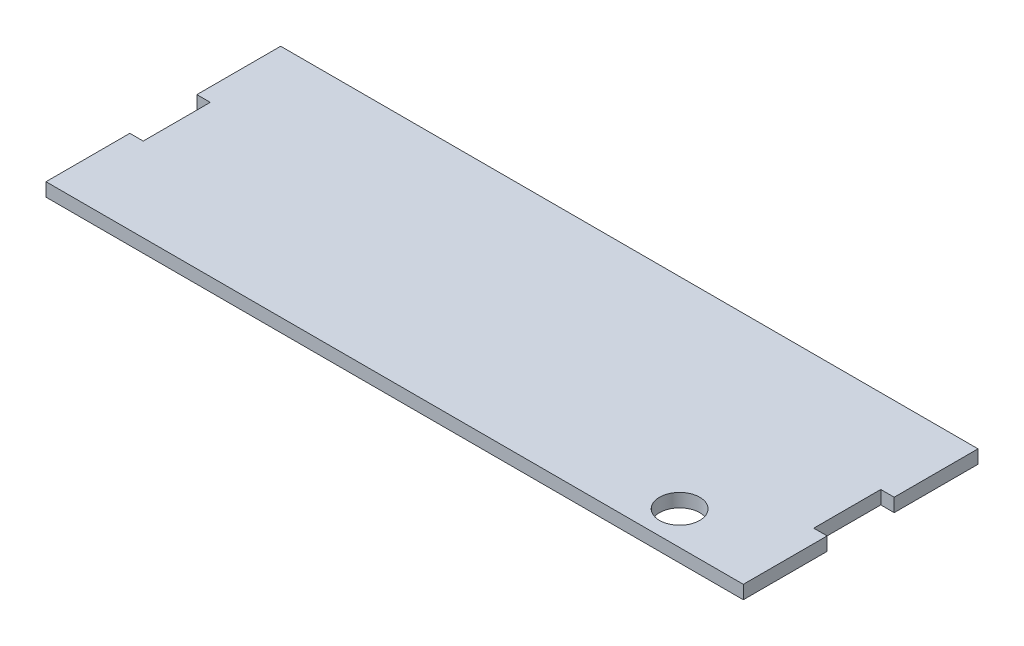
SolidWorks part; units mm, degrees
ref_plane "Front Plane" through (0, 0, 0) normal (0, 0, 1) x (1, 0, 0)
ref_plane "Top Plane" through (0, 0, 0) normal (0, 1, 0) x (1, 0, 0)
ref_plane "Right Plane" through (0, 0, 0) normal (1, 0, 0) x (0, 0, -1)
sketch "Sketch1" plane through (0, 0, 0) normal (0, 1, 0) x (1, 0, 0)
  line L1 (0, 0) -> (200, 0)
  line L2 (0, 0) -> (0, 70)
  line L3 (0, 70) -> (200, 70)
  line L4 (200, 0) -> (200, 70)
  line L5 (200, 70) -> (204, 70)
  line L6 (200, 70) -> (200, 45)
  line L7 (200, 45) -> (204, 45)
  line L8 (204, 70) -> (204, 45)
  line L9 (200, 0) -> (204, 0)
  line L10 (200, 0) -> (200, 25)
  line L11 (200, 25) -> (204, 25)
  line L12 (204, 0) -> (204, 25)
  line L13 (0, 0) -> (-4, 0)
  line L14 (0, 0) -> (0, 25)
  line L15 (0, 25) -> (-4, 25)
  line L16 (-4, 0) -> (-4, 25)
  line L17 (0, 70) -> (-4, 70)
  line L18 (0, 70) -> (0, 45)
  line L19 (0, 45) -> (-4, 45)
  line L20 (-4, 70) -> (-4, 45)
  circle A0 centre (175, 10) radius 6
  dimension "D11" = 12
  dimension "D12" = 10
  dimension "D13" = 25
  dimension "D1" = 200
  dimension "D2" = 20
  dimension "D3" = 4
  dimension "D4" = 4
  dimension "D5" = 4
  dimension "D6" = 4
  dimension "D7" = 25
  dimension "D8" = 25
  dimension "D9" = 25
  dimension "D10" = 25
extrude "Boss-Extrude1" add sketch "Sketch1" along normal blind 4 contours L1 L4 L3 L2 | L17 L20 L19 L2 | L16 L13 L2 L15 | L9 L12 L11 L4 | L8 L5 L4 L7
